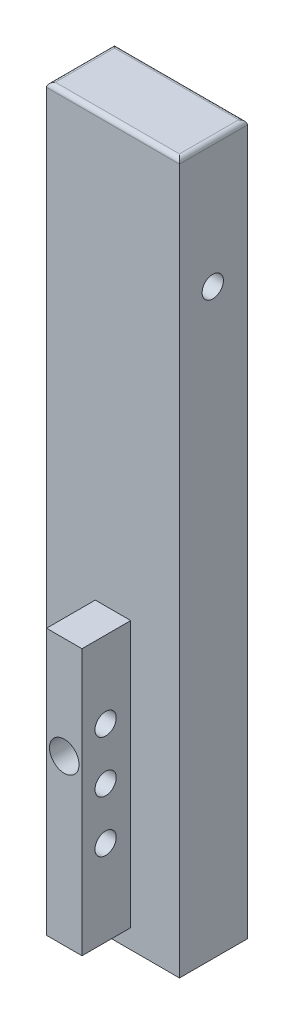
SolidWorks part; units mm, degrees
ref_plane "Plano frontal" through (0, 0, 0) normal (0, 0, 1) x (1, 0, 0)
ref_plane "Plano superior" through (0, 0, 0) normal (0, 1, 0) x (1, 0, 0)
ref_plane "Plano direito" through (0, 0, 0) normal (1, 0, 0) x (0, 0, -1)
sketch "Esboço1" plane through (0, 0, 0) normal (1, 0, 0) x (0, 0, -1)
  line L0 (0, 68.3784) -> (0, -51.6216)
  line L1 (0, -51.6216) -> (11.5, -51.6216)
  line L2 (11.5, -51.6216) -> (11.5, 68.3784)
  line L3 (11.5, 68.3784) -> (0, 68.3784)
  dimension "D1" = 120
  dimension "D2" = 11.5
extrude "Ressalto-extrusão1" add sketch "Esboço1" along normal blind 22.5
ref_plane "Plano1" through (8.25, 0, 0) normal (-1, 0, 0) x (0, 0, 1)
sketch "Esboço5" plane through (8.25, 0, 0) normal (-1, 0, 0) x (0, 0, 1)
  line L0 (0, -48.3716) -> (8.25, -48.3716)
  line L1 (0, 68.3784) -> (0, -51.6216) construction
  line L2 (8.25, -48.3716) -> (8.25, -3.3716)
  line L3 (0, -48.3716) -> (0, -3.3716)
  line L4 (8.25, -3.3716) -> (0, -3.3716)
  dimension "D1" = 8.25
  dimension "D2" = 45
extrude "Ressalto-extrusão2" add sketch "Esboço5" against normal blind 6
sketch "Esboço7" plane through (22.5, 0, 0) normal (1, 0, 0) x (0, 0, -1)
  line L0 (-8.25, -48.3716) -> (-8.25, -3.3716) construction
  line L1 (11.5, 68.3784) -> (0, 68.3784) construction
  line L2 (0, 68.3784) -> (0, -51.6216) construction
  line L4 (0, -48.3716) -> (-8.25, -48.3716) construction
  circle A0 centre (5.625, 46.8784) radius 1.8
  circle A1 centre (5.75, 30.6284) radius 1.8 construction
  circle A2 centre (5.75, 20.6284) radius 1.8 construction
  circle A3 centre (5.75, 0.6284) radius 1.8 construction
  circle A4 centre (-4.25, -33.8716) radius 1.8
  circle A5 centre (-4.25, -25.1216) radius 1.8
  circle A6 centre (-4.25, -16.3716) radius 1.8
  dimension "D1" = 3.6
  dimension "D2" = 3.6
  dimension "D3" = 3.6
  dimension "D4" = 3.6
  dimension "D6" = 37.75
  dimension "D7" = 47.75
  dimension "D9" = 3.6
  dimension "D10" = 3.6
  dimension "D11" = 3.6
  dimension "D14" = 32
  dimension "D5" = 21.5
  dimension "D8" = 67.75
  dimension "D12" = 14.5
  dimension "D13" = 23.25
  dimension "D15" = 4
  dimension "D16" = 5.625
extrude "Corte-extrusão1" cut sketch "Esboço7" against normal blind 30
sketch "Esboço10" plane through (0, 0, -11.5) normal (0, 0, -1) x (-1, 0, 0)
  line L0 (-22.5, -20.6216) -> (0, -20.6216) construction
  line L1 (-22.5, -51.6216) -> (-22.5, 68.3784) construction
  line L2 (0, -51.6216) -> (0, 68.3784) construction
  line L3 (-22.5, -51.6216) -> (0, -51.6216) construction
  circle A0 centre (-11.25, -20.6216) radius 2.5
  dimension "D1" = 5
  dimension "D2" = 31
extrude "Corte-extrusão3" cut sketch "Esboço10" against normal up to surface (19.75 mm away) up to face at (11.25, -25.8716, 8.25)
fillet "Fillet1" radius 0.75 4 edges at (11.25, 68.3784, -11.5) (22.5, 68.3784, -5.75) (11.25, 68.3784, 0) (0, 68.3784, -5.75)
